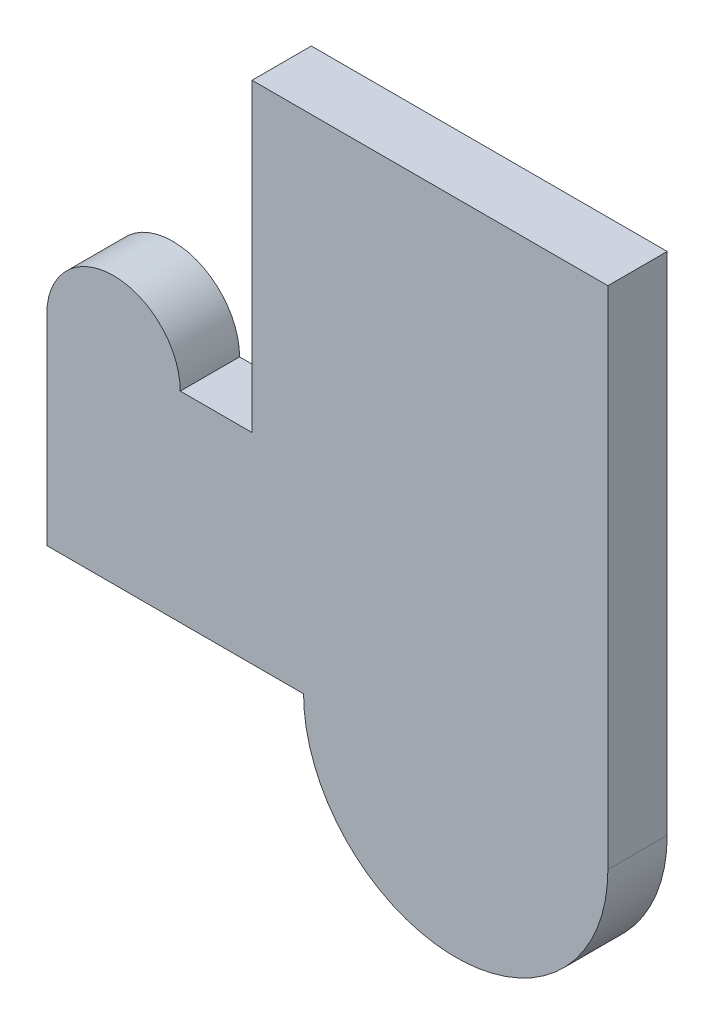
SolidWorks part; units mm, degrees
ref_plane "Front Plane" through (0, 0, 0) normal (0, 0, 1) x (1, 0, 0)
ref_plane "Top Plane" through (0, 0, 0) normal (0, 1, 0) x (1, 0, 0)
ref_plane "Right Plane" through (0, 0, 0) normal (1, 0, 0) x (0, 0, -1)
sketch "part1" plane through (0, 0, 0) normal (0, 0, 1) x (1, 0, 0)
  line L0 (0, 0) -> (0, 51.443)
  line L1 (0, 51.443) -> (60, 51.443)
  line L2 (60, 51.443) -> (60, -33.8054)
  line L3 (8.6906, -33.8054) -> (-34.6017, -33.8054)
  line L4 (-34.6017, -33.8054) -> (-34.6017, 0)
  line L5 (-12.1005, 0) -> (0, 0)
  arc A0 (60, -33.8054) -> (8.6906, -33.8054) centre (34.3453, -33.8054) cw
  arc A1 (-34.6017, 0) -> (-12.1005, 0) centre (-23.3511, 0) cw
  dimension "D3" = 25.6547
  dimension "D6" = 11.2506
  dimension "D1" = 60
  dimension "D2" = 85.2485
  dimension "D4" = 33.8054
  dimension "D5" = 43.2923
  dimension "D7" = 33.8054
extrude "Boss-Extrude1" add sketch "part1" along normal blind 10
